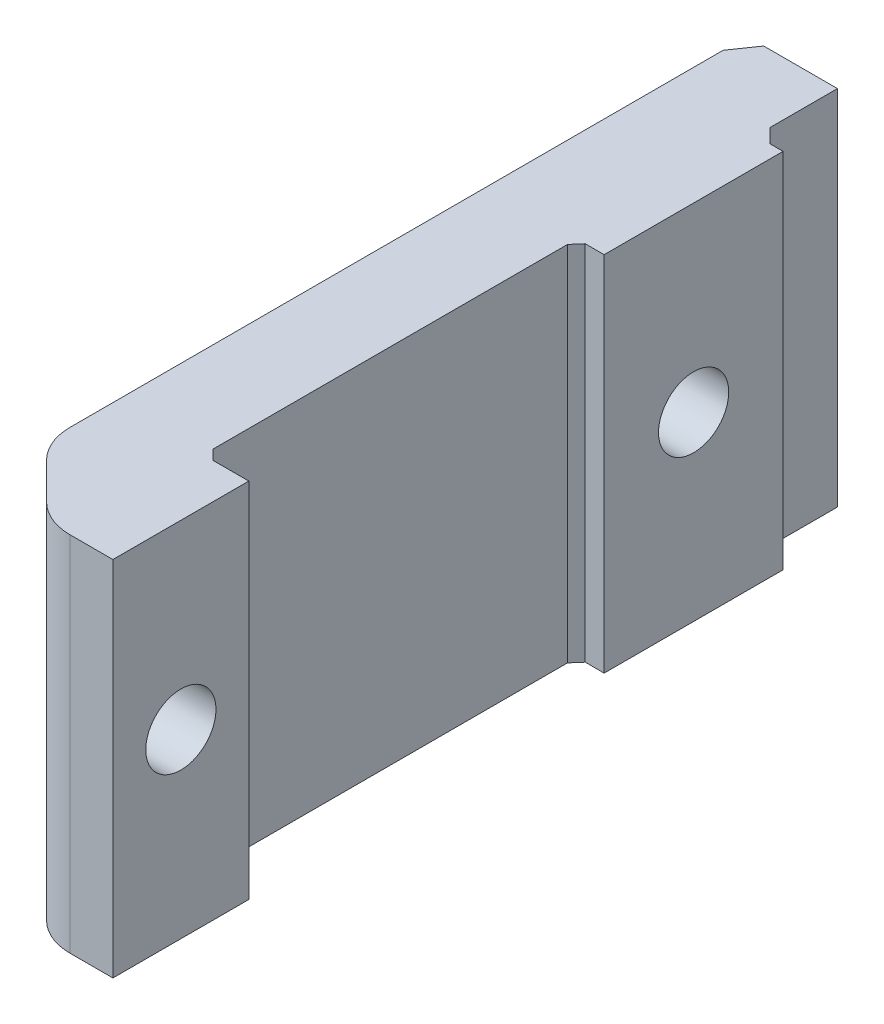
SolidWorks part; units mm, degrees
ref_plane "正面" through (0, 0, 0) normal (0, 0, 1) x (1, 0, 0)
ref_plane "平面" through (0, 0, 0) normal (0, 1, 0) x (1, 0, 0)
ref_plane "右側面" through (0, 0, 0) normal (1, 0, 0) x (0, 0, -1)
sketch "ｽｹｯﾁ1" plane through (0, 0, 0) normal (0, 1, 0) x (1, 0, 0)
  line L0 (1.311, 25.8969) -> (-1.9446, 25.8969)
  line L2 (-2.6769, 17.239) -> (-2.6769, -3.997)
  line L3 (-1.9446, -5.7647) -> (-0.3385, -7.3709)
  line L4 (1.4293, -8.1031) -> (3.3231, -8.1031)
  line L5 (3.3231, -8.1031) -> (3.3231, -2.1031)
  line L6 (3.3231, -2.1031) -> (1.7513, -2.1031)
  line L10 (2.5277, 14.472) -> (2.511, 14.3969)
  line L11 (2.511, 14.3969) -> (2.511, 22.2969)
  line L14 (1.311, 22.9228) -> (1.311, 25.8969)
  line L15 (2.511, 14.3969) -> (1.674, 14.3969)
  line L18 (1.7513, -2.1031) -> (1.311, -1.6628)
  line L20 (1.311, 22.9228) -> (1.9369, 22.2969)
  line L21 (1.9369, 22.2969) -> (2.511, 22.2969)
  line L27 (1.311, -1.6628) -> (1.311, 13.9784)
  line L28 (1.311, 13.9784) -> (1.674, 14.3969)
  line L29 (-2.6769, 17.239) -> (-2.6769, 24.8307)
  line L30 (-2.6769, 24.8307) -> (-2.6906, 24.8171)
  line L31 (-2.6906, 24.8171) -> (-1.9446, 25.8969)
  arc A0 (1.4293, -8.1031) -> (-0.3385, -7.3709) centre (1.4293, -5.6031) cw
  arc A1 (-1.9446, -5.7647) -> (-2.6769, -3.997) centre (-0.1769, -3.997) cw
  dimension "D7" = 2.5
  dimension "D1" = 34
  dimension "D2" = 6
  dimension "D3" = 16.5
  dimension "D4" = 6
  dimension "D5" = 7.9
  dimension "D6" = 1.2
  dimension "D8" = 1.0798
  dimension "D9" = 0.7459
  dimension "D10" = 0.6259
  dimension "D11" = 0.6259
  dimension "D12" = 0.4185
  dimension "D13" = 0.363
extrude "ﾎﾞｽ - 押し出し1" add sketch "ｽｹｯﾁ1" along normal blind 16
sketch "ｽｹｯﾁ2" plane through (2.511, 0, 0) normal (1, 0, 0) x (0, 0, -1)
  line L0 (-8.1031, 16) -> (-8.1031, 0) construction
  line L1 (22.2969, 16) -> (22.2969, 0) construction
  circle A0 centre (18.3469, 8) radius 1.55
  circle A1 centre (-5.1031, 8) radius 1.55
  dimension "D1" = 3
  dimension "D2" = 3.95
extrude "ｶｯﾄ - 押し出し1" cut sketch "ｽｹｯﾁ2" against normal through all both and the other way through all contours A0 | A1
